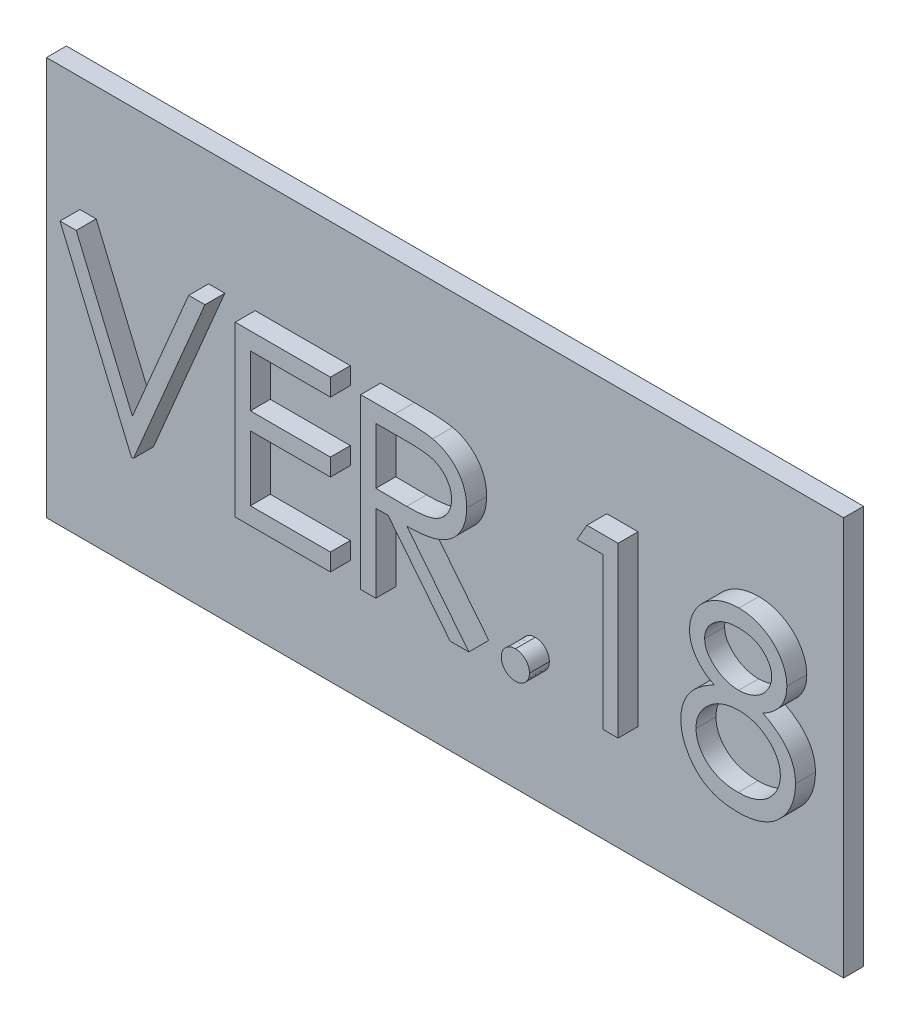
SolidWorks part; units mm, degrees
ref_plane "정면" through (0, 0, 0) normal (0, 0, 1) x (1, 0, 0)
ref_plane "윗면" through (0, 0, 0) normal (0, 1, 0) x (1, 0, 0)
ref_plane "우측면" through (0, 0, 0) normal (1, 0, 0) x (0, 0, -1)
sketch "스케치1" plane through (0, 0, 0) normal (0, 0, 1) x (1, 0, 0)
  line L1 (-10, -5) -> (10, -5)
  line L2 (-10, -5) -> (-10, 5)
  line L3 (-10, 5) -> (10, 5)
  line L4 (10, -5) -> (10, 5)
  line L5 (-10, -5) -> (10, 5) construction
  line L6 (-10, 5) -> (10, -5) construction
  point P0 (0, 0)
  dimension "D1" = 20
  dimension "D2" = 10
extrude "보스-돌출1" add sketch "스케치1" along normal blind 0.5
sketch "스케치2" plane through (0, 0, 0.5) normal (0, 0, 1) x (1, 0, 0)
  text T0 "VER.18" font "Century Gothic" height in points 16
extrude "보스-돌출2" add sketch "스케치2" along normal blind 0.5
